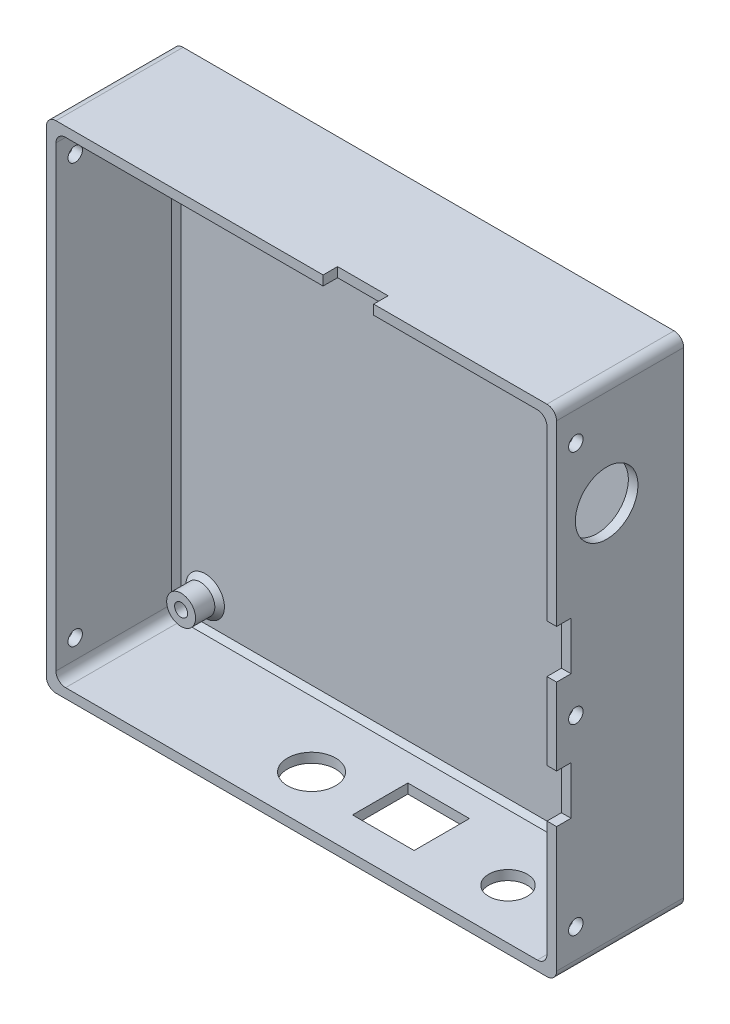
SolidWorks part; units mm, degrees
ref_plane "Спереди" through (0, 0, 0) normal (0, 0, 1) x (1, 0, 0)
ref_plane "Сверху" through (0, 0, 0) normal (0, 1, 0) x (1, 0, 0)
ref_plane "Справа" through (0, 0, 0) normal (1, 0, 0) x (0, 0, -1)
other "Configuration Table"
sketch "Эскиз1" plane through (0, 0, 0) normal (0, 0, 1) x (1, 0, 0)
  line L5 (-53, -51.5) -> (53, -51.5)
  line L6 (-53, -51.5) -> (-53, 51.5)
  line L11 (-53, 51.5) -> (53, 51.5)
  line L12 (53, -51.5) -> (53, 51.5)
  line L13 (-53, -51.5) -> (53, 51.5) construction
  line L14 (-53, 51.5) -> (53, -51.5) construction
  line L15 (-51, -49.5) -> (51, -49.5)
  line L16 (-51, -49.5) -> (-51, 49.5)
  line L17 (-51, 49.5) -> (51, 49.5)
  line L18 (51, -49.5) -> (51, 49.5)
  line L19 (-51, -49.5) -> (51, 49.5) construction
  line L20 (-51, 49.5) -> (51, -49.5) construction
  point P0 (0, 0)
  point P6 (0, 0)
  dimension "D1" = 103
  dimension "D2" = 106
  dimension "D3" = 2
  dimension "D4" = 2
extrude "Бобышка-Вытянуть1" add sketch "Эскиз1" along normal blind 25
sketch "Эскиз2" plane through (0, 0, 0) normal (0, 0, -1) x (-1, 0, 0)
  line L4 (-53, 51.5) -> (-53, -51.5)
  line L5 (-53, -51.5) -> (53, -51.5)
  line L6 (53, -51.5) -> (53, 51.5)
  line L7 (53, 51.5) -> (-53, 51.5)
  line L8 (-53, 51.5) -> (-53, -51.5)
  line L9 (-53, -51.5) -> (53, -51.5)
  line L10 (53, -51.5) -> (53, 51.5)
  line L11 (53, 51.5) -> (-53, 51.5)
  dimension "D1" = 0
extrude "Бобышка-Вытянуть2" add sketch "Эскиз2" along normal blind 1.4
sketch "Эскиз3" plane through (0, 0, 0) normal (0, 0, 1) x (1, 0, 0)
  line L0 (0, 51.5) -> (0, -51.5) construction
  line L1 (-45, -43.5) -> (45, -43.5) construction
  line L2 (-45, -43.5) -> (-45, 39.5) construction
  line L3 (-45, 39.5) -> (45, 39.5) construction
  line L4 (45, -43.5) -> (45, 39.5) construction
  line L5 (-45, -43.5) -> (45, 39.5) construction
  line L6 (-45, 39.5) -> (45, -43.5) construction
  line L7 (53, 51.5) -> (-53, 51.5) construction
  line L8 (-53, -51.5) -> (53, -51.5) construction
  circle A0 centre (-45, 39.5) radius 3
  circle A1 centre (45, 39.5) radius 3
  circle A2 centre (-45, -43.5) radius 3
  circle A3 centre (45, -43.5) radius 3
  circle A4 centre (-45, 39.5) radius 1.35
  circle A5 centre (45, 39.5) radius 1.35
  circle A6 centre (-45, -43.5) radius 1.35
  circle A7 centre (45, -43.5) radius 1.35
  point P0 (-2.3667, -6.7481)
  point P14 (0, -2)
  dimension "D3" = 6
  dimension "D4" = 2.7
  dimension "D1" = 90
  dimension "D2" = 83
  dimension "D5" = 8
extrude "Бобышка-Вытянуть3" add sketch "Эскиз3" along normal blind 5
sketch "Эскиз4" plane through (0, -51.5, 0) normal (0, -1, 0) x (1, 0, 0)
  line L0 (53, 25) -> (53, -1.4) construction
  line L1 (3.7, 18.1) -> (16.5, 18.1)
  line L2 (3.7, 18.1) -> (3.7, 6.6)
  line L3 (3.7, 6.6) -> (16.5, 6.6)
  line L4 (16.5, 18.1) -> (16.5, 6.6)
  line L5 (53, -1.4) -> (-53, -1.4) construction
  dimension "D1" = 36.5
  dimension "D2" = 12.8
  dimension "D3" = 11.5
  dimension "D4" = 8
extrude "Вырез-Вытянуть1" cut sketch "Эскиз4" against normal up to surface (101 mm away) up to face at (0, 49.5, 12.5)
fillet "Скругление1" radius 2 8 edges at (-53, -51.5, 11.8) (53, -51.5, 11.8) (53, 51.5, 11.8) (-53, 51.5, 11.8) (-51, -49.5, 12.5) (-51, 49.5, 12.5) (51, 49.5, 12.5) (51, -49.5, 12.5)
chamfer "Фаска1" distance 1 angle 45 12 edges at (-50.4142, 48.9142, 0) (0, 49.5, 0) (50.4142, 48.9142, 0) (51, 0, 0) (50.4142, -48.9142, 0) (0, -49.5, 0) (-50.4142, -48.9142, 0) (-51, 0, 0) (-48, 39.5, 0) (42, 39.5, 0) (-48, -43.5, 0) (42, -43.5, 0)
sketch "Эскиз5" plane through (0, -51.5, 0) normal (0, -1, 0) x (1, 0, 0)
  line L0 (3.7, 14.6) -> (48.1817, 14.6) construction
  line L1 (3.7, 18.1) -> (3.7, 6.6) construction
  line L2 (3.7, 14.6) -> (-48.4627, 14.6) construction
  line L3 (16.5, 6.6) -> (16.5, 18.1) construction
  line L4 (51, -1.4) -> (-51, -1.4) construction
  circle A0 centre (32.5, 14.6) radius 4
  circle A1 centre (-8.3, 14.6) radius 5
  dimension "D1" = 8
  dimension "D4" = 10
  dimension "D2" = 16
  dimension "D3" = 12
  dimension "D5" = 16
extrude "Вырез-Вытянуть2" cut sketch "Эскиз5" against normal up to surface (2 mm away) up to face at (10.1, -49.5, 12.35)
sketch "Эскиз6" plane through (53, 0, 0) normal (1, 0, 0) x (0, 0, -1)
  line L0 (-25, -49.5) -> (-25, 49.5) construction
  line L1 (-25, -13.5) -> (-22, -13.5)
  line L2 (-25, -13.5) -> (-25, -23.5)
  line L3 (-25, -23.5) -> (-22, -23.5)
  line L4 (-22, -13.5) -> (-22, -23.5)
  line L5 (1.4, -51.5) -> (-25, -51.5) construction
  line L6 (-25, 12.5) -> (-22, 12.5)
  line L7 (-25, 12.5) -> (-25, 2.5)
  line L8 (-25, 2.5) -> (-22, 2.5)
  line L9 (-22, 12.5) -> (-22, 2.5)
  dimension "D1" = 3
  dimension "D2" = 28
  dimension "D3" = 16
  dimension "D4" = 10
extrude "Вырез-Вытянуть3" cut sketch "Эскиз6" against normal up to surface (2 mm away) up to face at (51, 0, 13)
sketch "Эскиз8" plane through (53, 0, 0) normal (1, 0, 0) x (0, 0, -1)
  line L0 (-21, 51.5) -> (-21, -51.2985) construction
  line L1 (-25, 51.5) -> (1.4, 51.5) construction
  line L2 (-25, 12.5) -> (-25, 49.5) construction
  line L3 (1.4, -51.5) -> (-25, -51.5) construction
  circle A0 centre (-21, 43.5) radius 1.5
  circle A1 centre (-21, -43.5) radius 1.5
  dimension "D4" = 3
  dimension "D1" = 4
  dimension "D2" = 8
  dimension "D3" = 8
extrude "Вырез-Вытянуть4" cut sketch "Эскиз8" against normal through all
sketch "Эскиз9" plane through (53, 0, 0) normal (1, 0, 0) x (0, 0, -1)
  line L0 (-21, 43.5) -> (-21, -43.5) construction
  line L1 (1.4, -51.5) -> (-25, -51.5) construction
  circle A0 centre (-21, -5.5) radius 1.5
  dimension "D1" = 3
  dimension "D2" = 46
extrude "Вырез-Вытянуть5" cut sketch "Эскиз9" against normal up to surface (2 mm away) up to face at (51, 43.5, 22.5)
sketch "Эскиз10" plane through (0, 51.5, 0) normal (0, 1, 0) x (1, 0, 0)
  line L0 (51, -25) -> (-51, -25) construction
  line L1 (4.5, -25) -> (15, -25)
  line L2 (4.5, -25) -> (4.5, -22)
  line L3 (4.5, -22) -> (15, -22)
  line L4 (15, -25) -> (15, -22)
  line L5 (53, -22) -> (53, -25) construction
  line L6 (53, 1.4) -> (53, -25) construction
  dimension "D1" = 10.5
  dimension "D2" = 38
extrude "Вырез-Вытянуть6" cut sketch "Эскиз10" against normal up to surface (2 mm away) up to face at (0, 49.5, 13)
sketch "Эскиз11" plane through (53, -1.5, 0) normal (-1, 0, 0) x (0, 1, 0)
  line L2 (51, -25) -> (51, 1.4) construction
  line L3 (-48, 1.4) -> (51, 1.4) construction
  circle A0 centre (31, -14.6) radius 6.5
  dimension "D1" = 13
  dimension "D2" = 16
  dimension "D3" = 20
extrude "Вырез-Вытянуть7" cut sketch "Эскиз11" along normal up to surface (2 mm away) up to face at (51, -5.5, 22.5)
